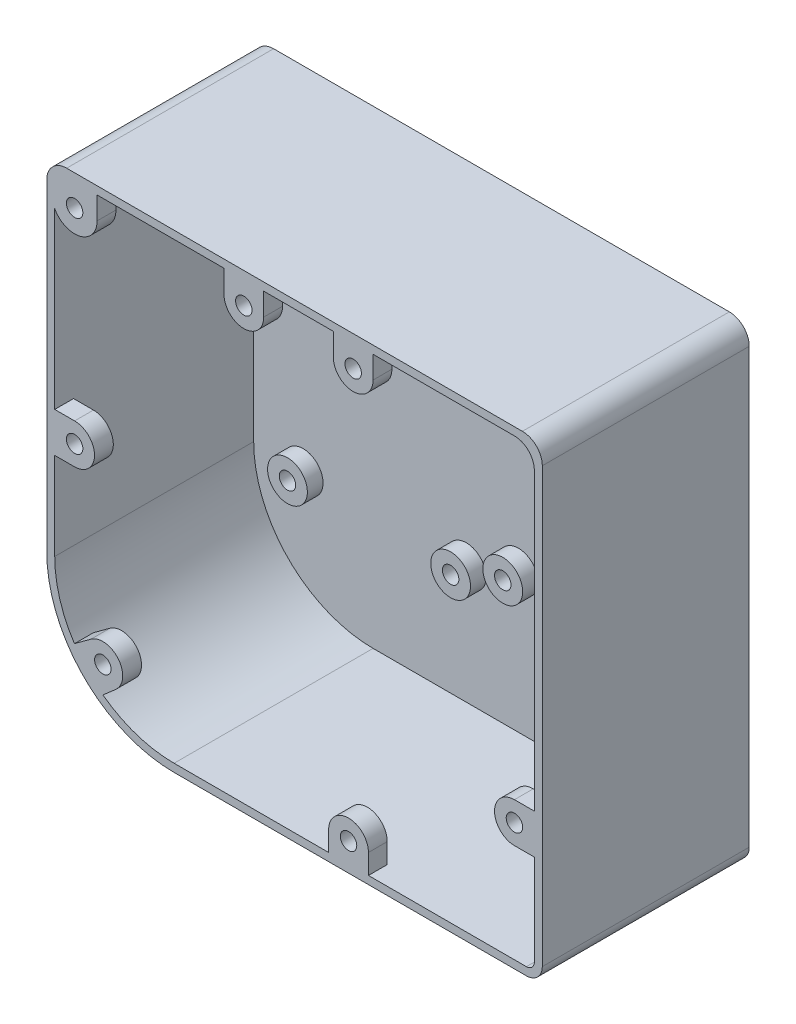
SolidWorks part; units mm, degrees
material "Custom Plastic"
ref_plane "X-Y Datum" through (0, 0, 0) normal (0, 0, 1) x (1, 0, 0)
ref_plane "X-Z Datum" through (0, 0, 0) normal (0, 1, 0) x (1, 0, 0)
ref_plane "Y-Z Datum" through (0, 0, 0) normal (1, 0, 0) x (0, 0, -1)
sketch "Sketch1" plane through (0, 0, 0) normal (0, 0, 1) x (1, 0, 0)
  line L0 (1.8162, 48.1563) -> (125.4513, 48.1563) construction
  line L1 (24.3593, 48.1563) -> (24.3593, 120.2923) construction
  line L3 (24.3593, 120.2923) -> (125.4513, 120.2923) construction
  line L8 (125.4513, 48.1563) -> (125.4513, 120.2923) construction
  line L33 (24.3593, 120.2923) -> (1.8162, 120.2923) construction
  line L34 (24.3593, 120.2923) -> (24.3593, 48.1563) construction
  line L35 (63.6337, 48.1563) -> (63.6337, 43.0763) construction
  line L36 (1.8162, 120.2923) -> (1.8162, 48.1563) construction
  line L37 (8.9602, -19.4077) -> (8.9602, 43.0763) construction
  line L38 (8.9602, -19.4077) -> (118.3072, -19.4077) construction
  line L39 (118.3072, -19.4077) -> (118.3072, 43.0763) construction
  line L40 (118.3072, 43.0763) -> (8.9602, 43.0763) construction
  line L41 (1.8162, 120.2923) -> (1.8162, 122.8323) construction
  line L42 (1.8162, 120.2923) -> (0.5462, 120.2923) construction
  line L43 (1.8162, 48.1563) -> (0.5462, 48.1563) construction
  line L44 (8.9602, -19.4077) -> (8.9602, -21.9477) construction
  line L45 (125.4513, 120.2923) -> (127.9913, 120.2923) construction
  line L47 (0.5462, 122.8323) -> (127.9913, 122.8323)
  line L48 (0.5462, 122.8323) -> (0.5462, -21.9477)
  line L49 (0.5462, -21.9477) -> (127.9913, -21.9477)
  line L50 (127.9913, 122.8323) -> (127.9913, -21.9477)
  circle A17 centre (30.4553, 114.1963) radius 2.1 construction
  circle A18 centre (119.8633, 115.2123) radius 2.1 construction
  circle A19 centre (119.6813, 54.2533) radius 2.1 construction
  circle A20 centre (29.4393, 53.2363) radius 2.1 construction
  circle A21 centre (13.7862, -13.9467) radius 2.1 construction
  circle A22 centre (13.7862, -13.9467) radius 2.1 construction
  circle A23 centre (13.7672, 38.1213) radius 2.1 construction
  circle A24 centre (113.4812, -13.9467) radius 2.1 construction
  circle A25 centre (113.4812, 37.9963) radius 2.1 construction
sketch "Sketch2" plane through (0, 0, 0) normal (0, 0, 1) x (1, 0, 0)
  line L4 (127.9913, 122.8323) -> (127.9913, 50.0171)
  line L6 (56.0834, 120.2923) -> (56.0834, 122.8323)
  line L7 (-15.891, 122.8323) -> (-15.891, 50.0171)
  line L8 (127.9913, 50.0171) -> (-15.891, 50.0171)
  line L9 (115.3693, 122.8323) -> (-15.891, 50.0171) construction
  line L10 (-3.269, 122.8323) -> (127.9913, 50.0171) construction
  line L11 (56.0834, 122.8323) -> (-15.891, 122.8323)
  line L12 (56.0834, 122.8323) -> (127.9913, 122.8323)
  circle A7 centre (11.609, 89.9257) radius 27.5
  circle A8 centre (100.509, 89.979) radius 27.5
  circle A9 centre (56.0501, 79.7923) radius 6.477
  circle A10 centre (56.0679, 100.1123) radius 6.477
  circle A11 centre (36.9798, 56.4941) radius 6.477
  circle A12 centre (56.0346, 62.0123) radius 2.4
  circle A13 centre (56.0834, 117.8923) radius 2.4
  point P14 (56.0501, 89.9257)
sketch "Sketch5" plane through (0, 0, 0) normal (0, 0, 1) x (1, 0, 0)
  line L0 (11.609, 89.9257) -> (-7.8365, 109.3711) construction
  line L5 (-7.8365, 109.3711) -> (-14.1227, 115.6573) construction
  line L6 (100.509, 89.979) -> (119.9545, 109.4244) construction
  line L7 (119.9545, 109.4244) -> (126.2407, 115.7106) construction
  line L8 (100.509, 89.979) -> (81.0636, 109.4244) construction
  line L9 (81.0636, 109.4244) -> (74.7774, 115.7106) construction
  line L10 (11.609, 89.9257) -> (31.0544, 109.3711) construction
  line L11 (31.0544, 109.3711) -> (37.3406, 115.6573) construction
  line L12 (-20.4727, 50.4423) -> (140.3848, 50.4423) construction
  line L13 (-20.4727, 122.8323) -> (132.5907, 122.8323)
  line L14 (-20.4727, 122.8323) -> (-20.4727, -21.9477)
  line L15 (-20.4727, -21.9477) -> (132.5907, -21.9477)
  line L16 (132.5907, 122.8323) -> (132.5907, -21.9477)
  circle A0 centre (126.2407, -14.826) radius 6.35 construction
  circle A2 centre (-14.1227, -14.7726) radius 6.35 construction
  circle A4 centre (11.609, 89.9257) radius 27.5 construction
  circle A5 centre (-14.1227, 115.6573) radius 6.35 construction
  circle A6 centre (100.509, 89.979) radius 27.5 construction
  circle A7 centre (126.2407, 115.7106) radius 6.35 construction
  circle A8 centre (74.7774, 115.7106) radius 6.35 construction
  circle A9 centre (37.3406, 115.6573) radius 6.35 construction
  circle A11 centre (126.2407, 50.4423) radius 6.35 construction
  circle A12 centre (-14.1227, 50.4423) radius 6.35 construction
extrude "Boss-Extrude4" add sketch "Sketch5" along normal blind 63.5
fillet "Fillet1" radius 38.1 1 edges at (-20.4727, -21.9477, 31.75)
fillet "Fillet2" radius 2.54 1 edges at (132.5907, -21.9477, 31.75)
shell "Shell3" thickness 2.54
sketch "Sketch7" plane through (0, 0, 0) normal (0, 0, 1) x (1, 0, 0)
  line L0 (118.2817, 122.1973) -> (130.0507, 122.1973) construction
  line L1 (57.9147, 118.1542) -> (57.9147, 17.0622) construction
  line L2 (57.9147, 118.1542) -> (130.0507, 118.1542) construction
  line L3 (130.0507, 118.1542) -> (130.0507, 17.0622) construction
  line L4 (57.9147, 17.0622) -> (130.0507, 17.0622) construction
  line L5 (130.0507, 118.1542) -> (130.0507, 140.6973) construction
  line L6 (130.0507, 118.1542) -> (57.9147, 118.1542) construction
  line L7 (57.9147, 118.1542) -> (57.9147, 140.6973) construction
  line L8 (130.0507, 140.6973) -> (57.9147, 140.6973) construction
  line L9 (52.8347, 10.9453) -> (-9.6493, 10.9453) construction
  line L10 (52.8347, 10.9453) -> (52.8347, 120.2923) construction
  line L11 (118.2817, 122.1973) -> (57.9147, 122.1973) construction
  line L12 (52.8347, 120.2923) -> (-9.6493, 120.2923) construction
  line L13 (-9.6493, 120.2923) -> (-9.6493, 10.9453) construction
  line L14 (132.5907, 122.8323) -> (132.5907, 122.1973) construction
  line L15 (132.5907, -19.4077) -> (132.5907, 122.8323) construction
  line L16 (132.5907, 122.1973) -> (130.0507, 122.1973) construction
  circle A0 centre (123.9547, 111.8042) radius 2.1 construction
  circle A1 centre (124.9707, 22.3962) radius 2.1 construction
  circle A2 centre (64.0117, 22.5782) radius 2.1 construction
  circle A3 centre (62.9947, 112.8202) radius 2.1 construction
  circle A4 centre (62.9947, 112.8202) radius 6.35
  circle A5 centre (123.9547, 111.8042) radius 6.35
  circle A6 centre (64.0117, 22.5782) radius 6.35
  circle A7 centre (124.9707, 22.3962) radius 6.35
  circle A8 centre (47.3737, 15.7713) radius 2.1 construction
  circle A9 centre (47.3737, 15.7713) radius 2.1 construction
  circle A10 centre (-4.6943, 15.7523) radius 2.1 construction
  circle A11 centre (47.3737, 115.4663) radius 2.1 construction
  circle A12 centre (-4.5693, 115.4663) radius 2.1 construction
  circle A13 centre (-4.5693, 115.4663) radius 6.35
  circle A14 centre (47.3737, 115.4663) radius 6.35
  circle A15 centre (-4.6943, 15.7523) radius 6.35
  circle A16 centre (47.3737, 15.7713) radius 6.35
extrude "Boss-Extrude5" add sketch "Sketch7" along normal blind 5
sketch "Sketch8" plane through (0, 0, 5) normal (0, 0, 1) x (1, 0, 0)
  circle A0 centre (-4.6943, 15.7523) radius 2.625
  circle A1 centre (47.3737, 15.7713) radius 2.625
  circle A2 centre (64.0117, 22.5782) radius 2.625
  circle A3 centre (124.9707, 22.3962) radius 2.625
  circle A4 centre (47.3737, 115.4663) radius 2.625
  circle A5 centre (-4.5693, 115.4663) radius 2.625
  circle A6 centre (62.9947, 112.8202) radius 2.625
  circle A7 centre (123.9547, 111.8042) radius 2.625
extrude "Cut-Extrude1" cut sketch "Sketch8" against normal blind 5
sketch "Sketch9" plane through (0, 0, 63.5) normal (0, 0, 1) x (1, 0, 0)
  line L0 (-6.9476, 115.6573) -> (-6.9476, 122.8323)
  line L1 (-20.4727, 122.8323) -> (132.5907, 122.8323) construction
  line L2 (-6.9476, 122.8323) -> (-20.4727, 122.8323)
  line L3 (-20.4727, 115.6573) -> (-20.4727, 122.8323)
  line L4 (-20.4727, 122.8323) -> (-20.4727, -21.9477) construction
  line L5 (-20.4727, 115.6573) -> (-20.4727, 112.3168)
  line L6 (33.5306, 115.6573) -> (33.5306, 122.8323)
  line L7 (33.5306, 122.8323) -> (46.2306, 122.8323)
  line L8 (46.2306, 122.8323) -> (46.2306, 115.6573)
  line L9 (68.4274, 115.7106) -> (68.4274, 122.8323)
  line L10 (68.4274, 122.8323) -> (81.1274, 122.8323)
  line L11 (81.1274, 122.8323) -> (81.1274, 115.7106)
  line L16 (132.5907, 122.8323) -> (132.5907, -21.9477) construction
  line L19 (126.2407, 22.2968) -> (132.5907, 22.2968)
  line L20 (126.2407, 9.5968) -> (132.5907, 9.5968)
  line L21 (132.5907, 9.5968) -> (132.5907, 22.2968)
  line L22 (-8.8805, -0.8964) -> (-14.1227, -4.7422)
  line L23 (-0.9351, -10.7884) -> (-5.0891, -14.4349)
  line L24 (-14.1227, 56.7923) -> (-20.4727, 56.7923)
  line L25 (-14.1227, 44.0923) -> (-20.4727, 44.0923)
  line L26 (-20.4727, 56.7923) -> (-20.4727, 44.0923)
  line L31 (73.2964, -21.9477) -> (73.2964, -15.5977) construction
  line L32 (-20.4727, -21.9477) -> (132.5907, -21.9477) construction
  line L33 (66.9464, -15.5977) -> (66.9464, -21.9477)
  line L34 (79.6464, -15.5977) -> (79.6464, -21.9477)
  line L35 (66.9464, -21.9477) -> (79.6464, -21.9477)
  arc A0 (-20.4727, 112.3168) -> (-6.9476, 115.6573) centre (-14.1227, 115.6573) ccw
  arc A1 (33.5306, 115.6573) -> (46.2306, 115.6573) centre (39.8806, 115.6573) ccw
  arc A2 (-14.1227, 44.0923) -> (-14.1227, 56.7923) centre (-14.1227, 50.4423) ccw
  arc A3 (68.4274, 115.7106) -> (81.1274, 115.7106) centre (74.7774, 115.7106) ccw
  arc A6 (126.2407, 22.2968) -> (126.2407, 9.5968) centre (126.2407, 15.9468) ccw
  arc A7 (-0.9351, -10.7884) -> (-8.8805, -0.8964) centre (-5.1243, -6.0163) ccw
  arc A8 (-20.4727, 16.1523) -> (17.6273, -21.9477) centre (17.6273, 16.1523) ccw construction
  circle A9 centre (-14.1227, 115.6573) radius 6.35 construction
  arc A10 (-20.4727, 16.1523) -> (17.6273, -21.9477) centre (17.6273, 16.1523) ccw construction
  arc A11 (-14.1227, -4.7422) -> (-5.0891, -14.4349) centre (-3.6836, -4.069) ccw
  arc A13 (79.6464, -15.5977) -> (66.9464, -15.5977) centre (73.2964, -15.5977) ccw
  point P20 (-9.3134, -10.7884)
extrude "Boss-Extrude6" add sketch "Sketch9" against normal blind 6
fillet "Fillet3" radius 6.35 4 edges at (-20.4727, 122.8323, 28.75) (-23.0127, 125.3723, 30.48) (132.5907, 122.8323, 31.75) (135.1307, 125.3723, 30.48)
sketch "Sketch10" plane through (0, 0, 63.5) normal (0, 0, 1) x (1, 0, 0)
  circle A0 centre (-14.1227, 115.6573) radius 2.625
  circle A1 centre (39.8806, 115.6573) radius 2.625
  circle A2 centre (74.7774, 115.7106) radius 2.625
  circle A3 centre (-14.1227, 50.4423) radius 2.625
  circle A4 centre (-5.1243, -6.0163) radius 2.625
  circle A5 centre (73.2964, -15.5977) radius 2.625
  circle A6 centre (126.2407, 15.9468) radius 2.625
extrude "Cut-Extrude2" cut sketch "Sketch10" against normal up to surface (58.5 mm away) up to face at (49.9987, 115.4663, 5)
sketch "Sketch11" plane through (0, 0, 63.5) normal (0, 0, 1) x (1, 0, 0)
  line L0 (-16.6627, 125.3723) -> (128.7807, 125.3723)
  line L1 (135.1307, 119.0223) -> (135.1307, -19.4077)
  line L2 (130.0507, -24.4877) -> (17.6273, -24.4877)
  line L3 (-23.0127, 16.1523) -> (-23.0127, 119.0223)
  circle A0 centre (-14.1227, 115.6573) radius 2.625
  arc A1 (17.6273, -24.4877) -> (-23.0127, 16.1523) centre (17.6273, 16.1523) cw
  arc A2 (128.7807, 125.3723) -> (135.1307, 119.0223) centre (128.7807, 119.0223) cw
  arc A3 (-16.6627, 125.3723) -> (-23.0127, 119.0223) centre (-16.6627, 119.0223) ccw
  arc A4 (135.1307, -19.4077) -> (130.0507, -24.4877) centre (130.0507, -19.4077) cw
  circle A5 centre (100.509, 89.979) radius 27.5 construction
  circle A6 centre (56.0501, 79.7923) radius 6.477
  circle A7 centre (56.0346, 62.0123) radius 2.4
  circle A8 centre (56.0679, 100.1123) radius 6.477
  circle A9 centre (56.0834, 117.8923) radius 2.4
  circle A10 centre (11.609, 89.9257) radius 27.5 construction
  circle A11 centre (36.9798, 56.4941) radius 6.477
  circle A13 centre (39.8806, 115.6573) radius 2.625
  circle A14 centre (74.7774, 115.7106) radius 2.625
  circle A16 centre (-14.1227, 50.4423) radius 2.625
  circle A17 centre (-5.1243, -6.0163) radius 2.625
  circle A18 centre (73.2964, -15.5977) radius 2.625
  circle A19 centre (126.2407, 15.9468) radius 2.625
  dimension "D1" = 40.64
  dimension "D2" = 6.35
  dimension "D3" = 5.08
